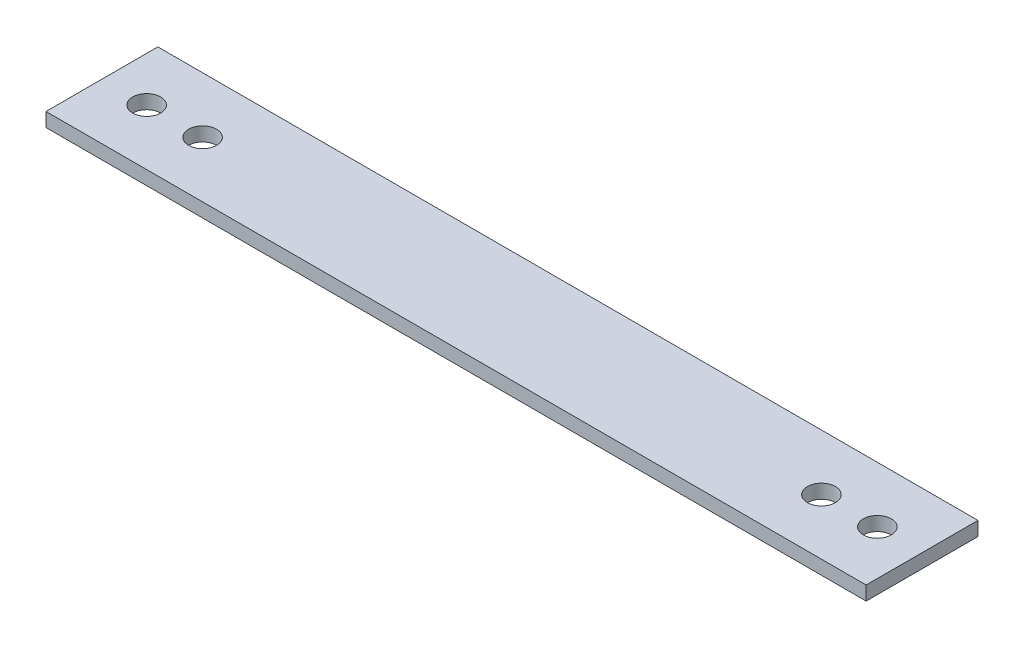
SolidWorks part; units mm, degrees
ref_plane "Front Plane" through (0, 0, 0) normal (0, 0, 1) x (1, 0, 0)
ref_plane "Top Plane" through (0, 0, 0) normal (0, 1, 0) x (1, 0, 0)
ref_plane "Right Plane" through (0, 0, 0) normal (1, 0, 0) x (0, 0, -1)
sketch "Sketch2" plane through (0, 0, 0) normal (0, 1, 0) x (1, 0, 0)
  line L1 (-139.7, -19.05) -> (139.7, -19.05)
  line L2 (-139.7, -19.05) -> (-139.7, 19.05)
  line L3 (-139.7, 19.05) -> (139.7, 19.05)
  line L4 (139.7, -19.05) -> (139.7, 19.05)
  line L5 (0, 19.05) -> (0, -19.05) construction
  line L6 (-139.7, 0) -> (139.7, 0) construction
  circle A0 centre (-124.46, 0) radius 4.7625
  circle A1 centre (-105.41, 0) radius 4.7625
  circle A2 centre (124.46, 0) radius 4.7625
  circle A3 centre (105.41, 0) radius 4.7625
  point P0 (0, 0)
  point P12 (0, 0)
  point P13 (0, 0)
  dimension "D3" = 9.525
  dimension "D1" = 38.1
  dimension "D2" = 279.4
  dimension "D4" = 19.05
  dimension "D5" = 15.24
extrude "Boss-Extrude1" add sketch "Sketch2" along normal blind 4.7625
